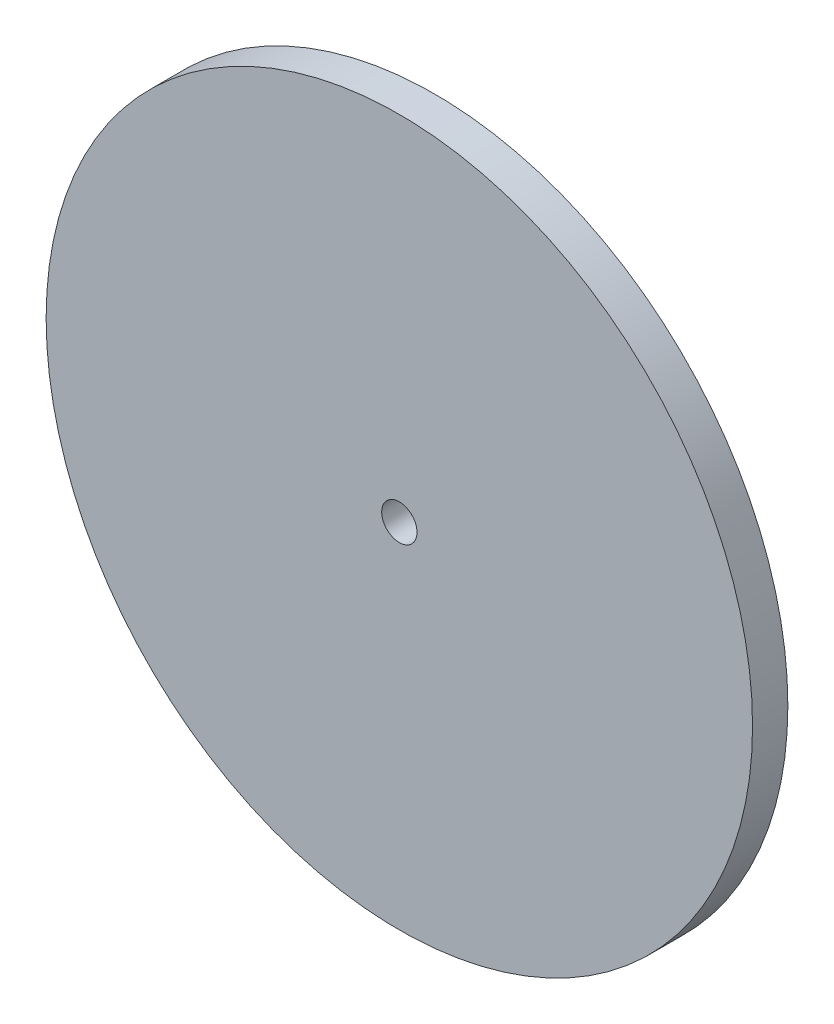
SolidWorks part; units mm, degrees
material "Cast Stainless Steel"
ref_plane "Front Plane" through (0, 0, 0) normal (0, 0, 1) x (1, 0, 0)
ref_plane "Top Plane" through (0, 0, 0) normal (0, 1, 0) x (1, 0, 0)
ref_plane "Right Plane" through (0, 0, 0) normal (1, 0, 0) x (0, 0, -1)
sketch "Sketch1" plane through (0, 0, 0) normal (0, 0, 1) x (1, 0, 0)
  circle A0 centre (0, 0) radius 500
  dimension "D1" = 1000
extrude "Boss-Extrude1" add sketch "Sketch1" along normal mid plane 50
sketch "Sketch2" plane through (0, 0, 25) normal (0, 0, 1) x (1, 0, 0)
  circle A0 centre (0, 0) radius 25
  dimension "D1" = 50
extrude "Cut-Extrude1" cut sketch "Sketch2" against normal up to next
